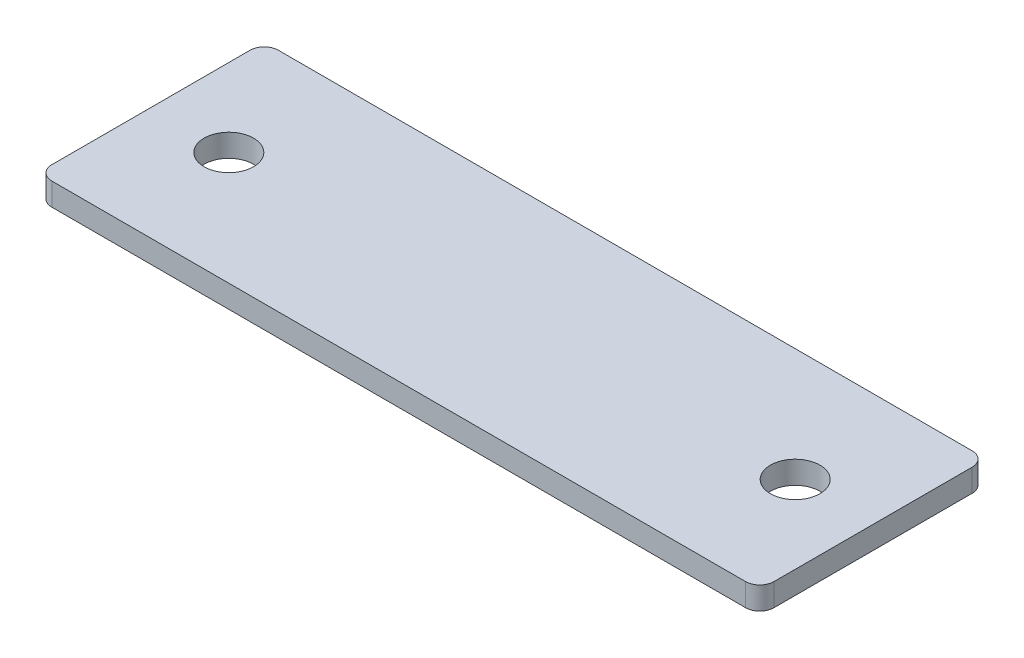
SolidWorks part; units mm, degrees
ref_plane "Front Plane" through (0, 0, 0) normal (0, 0, 1) x (1, 0, 0)
ref_plane "Top Plane" through (0, 0, 0) normal (0, 1, 0) x (1, 0, 0)
ref_plane "Right Plane" through (0, 0, 0) normal (1, 0, 0) x (0, 0, -1)
sketch "Sketch1" plane through (0, 0, 0) normal (0, 1, 0) x (1, 0, 0)
  line L0 (-20, 0) -> (20, 0) construction
  line L1 (-25.5, 8) -> (25.5, 8)
  line L2 (-25.5, 8) -> (-25.5, -8)
  line L3 (-25.5, -8) -> (25.5, -8)
  line L4 (25.5, 8) -> (25.5, -8)
  line L5 (-25.5, 8) -> (25.5, -8) construction
  line L6 (-25.5, -8) -> (25.5, 8) construction
  circle A0 centre (-20, 0) radius 1.75
  circle A1 centre (20, 0) radius 1.75
  point P0 (0, 0)
  point P8 (0, 0)
  dimension "D1" = 3.5
  dimension "D2" = 40
  dimension "D3" = 16
  dimension "D4" = 51
extrude "Boss-Extrude1" add sketch "Sketch1" along normal blind 1.6
fillet "Fillet1" radius 1 4 edges at (-25.5, 0.8, -8) (-25.5, 0.8, 8) (25.5, 0.8, -8) (25.5, 0.8, 8)
